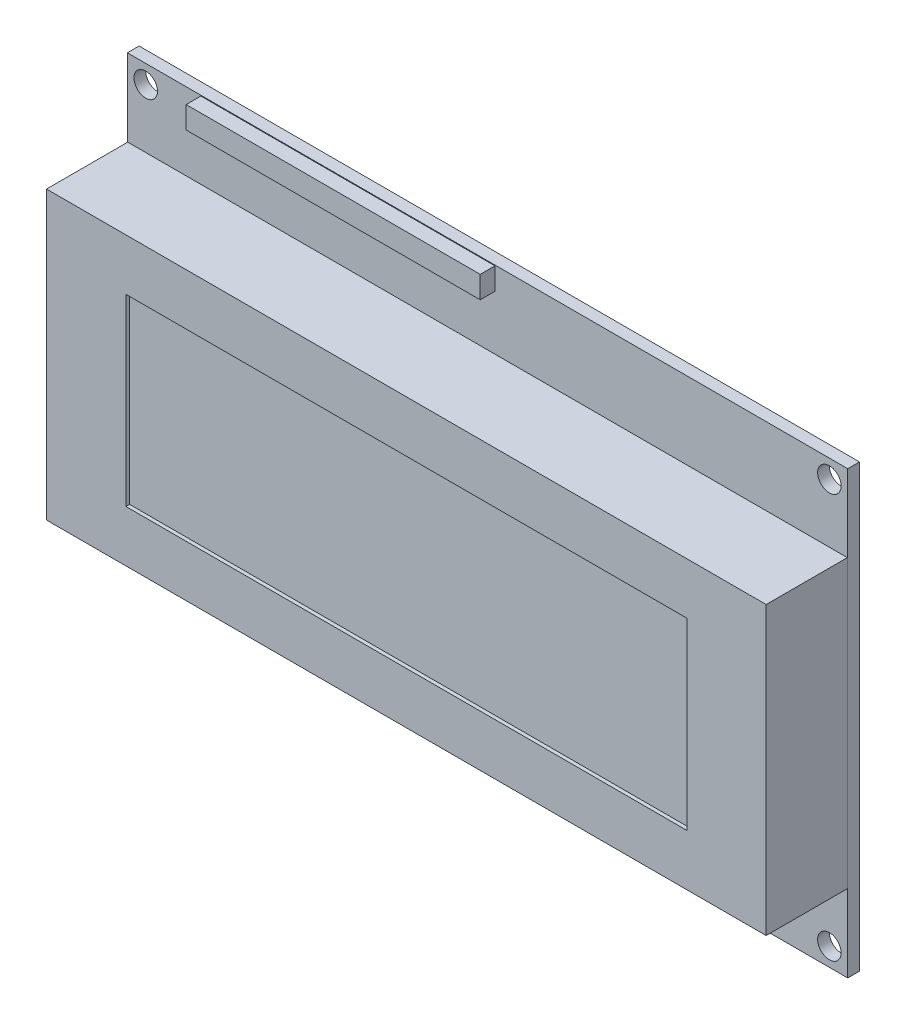
SolidWorks part; units mm, degrees
ref_plane "Plan de face" through (0, 0, 0) normal (0, 0, 1) x (1, 0, 0)
ref_plane "Plan de dessus" through (0, 0, 0) normal (0, 1, 0) x (1, 0, 0)
ref_plane "Plan de droite" through (0, 0, 0) normal (1, 0, 0) x (0, 0, -1)
sketch "Esquisse1" plane through (0, 0, 0) normal (0, 0, 1) x (1, 0, 0)
  line L1 (-49, 30) -> (49, 30)
  line L2 (-49, 30) -> (-49, -30)
  line L3 (-49, -30) -> (49, -30)
  line L4 (49, 30) -> (49, -30)
  line L5 (-49, 30) -> (49, -30) construction
  line L6 (-49, -30) -> (49, 30) construction
  point P0 (0, 0)
  dimension "D1" = 60
  dimension "D2" = 98
extrude "Boss.-Extru.1" add sketch "Esquisse1" along normal blind 1.6
sketch "Esquisse2" plane through (0, 0, 1.6) normal (0, 0, 1) x (1, 0, 0)
  line L1 (0, 14.1724) -> (0, 0) construction
  line L2 (0, 0) -> (11.4346, 0) construction
  line L3 (-49, 30) -> (-49, -30) construction
  circle A0 centre (-46.5, 27.5) radius 1.6
  circle A1 centre (-46.5, -27.5) radius 1.6
  circle A2 centre (46.5, -27.5) radius 1.6
  circle A3 centre (46.5, 27.5) radius 1.6
  point P14 (-44.2489, 28.0408)
  dimension "D1" = 3.2
  dimension "D2" = 3.2
  dimension "D3" = 3.2
  dimension "D4" = 3.2
  dimension "D5" = 55
  dimension "D6" = 2.5
extrude "Enlèv. mat.-Extru.1" cut sketch "Esquisse2" against normal through all
sketch "Esquisse3" plane through (0, 0, 1.6) normal (0, 0, 1) x (1, 0, 0)
  line L1 (-48.95, 19.5) -> (48.95, 19.5)
  line L2 (-48.95, 19.5) -> (-48.95, -19.5)
  line L3 (-48.95, -19.5) -> (48.95, -19.5)
  line L4 (48.95, 19.5) -> (48.95, -19.5)
  line L5 (-48.95, 19.5) -> (48.95, -19.5) construction
  line L6 (-48.95, -19.5) -> (48.95, 19.5) construction
  line L7 (49, 30) -> (-49, 30) construction
  line L8 (49, -30) -> (49, 30) construction
  point P0 (0, 0)
  dimension "D1" = 10.5
  dimension "D2" = 0.05
extrude "Boss.-Extru.2" add sketch "Esquisse3" along normal blind 11.05
sketch "Esquisse4" plane through (0, 0, 12.65) normal (0, 0, 1) x (1, 0, 0)
  line L1 (-38.15, 12.5) -> (38.15, 12.5)
  line L2 (-38.15, 12.5) -> (-38.15, -12.5)
  line L3 (-38.15, -12.5) -> (38.15, -12.5)
  line L4 (38.15, 12.5) -> (38.15, -12.5)
  line L5 (-38.15, 12.5) -> (38.15, -12.5) construction
  line L6 (-38.15, -12.5) -> (38.15, 12.5) construction
  point P0 (0, 0)
  dimension "D1" = 25
  dimension "D2" = 76.3
extrude "Enlèv. mat.-Extru.2" cut sketch "Esquisse4" against normal blind 0.5
sketch "Esquisse5" plane through (0, 0, 1.6) normal (0, 0, 1) x (1, 0, 0)
  line L1 (-39, 29.9) -> (1, 29.9)
  line L2 (-39, 29.9) -> (-39, 26.9)
  line L3 (-39, 26.9) -> (1, 26.9)
  line L4 (1, 29.9) -> (1, 26.9)
  line L5 (-49, 30) -> (-49, -30) construction
  line L6 (49, 30) -> (-49, 30) construction
  dimension "D1" = 3
  dimension "D2" = 40
  dimension "D3" = 10
  dimension "D4" = 0.1
extrude "Boss.-Extru.3" add sketch "Esquisse5" along normal blind 2
